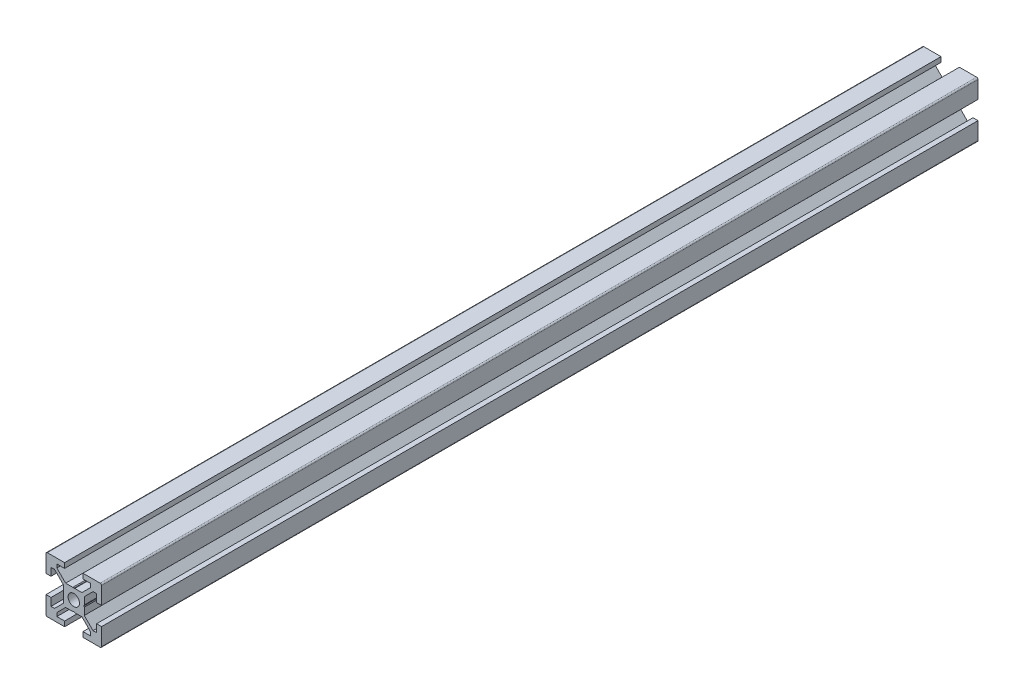
SolidWorks part; units mm, degrees
ref_plane "Front Plane" through (0, 0, 0) normal (0, 0, 1) x (1, 0, 0)
ref_plane "Top Plane" through (0, 0, 0) normal (0, 1, 0) x (1, 0, 0)
ref_plane "Right Plane" through (0, 0, 0) normal (1, 0, 0) x (0, 0, -1)
sketch "Sketch1" plane through (0, 0, 0) normal (0, 0, 1) x (1, 0, 0)
  line L0 (-3.3, 10) -> (-3.3, 8.2)
  line L1 (0, 0) -> (50000, 0) construction
  line L2 (-10, 3.3) -> (-10, 10)
  line L3 (-10, 10) -> (-3.3, 10)
  line L4 (0, 0) -> (0, 50000) construction
  line L5 (-10, -10) -> (10, 10) construction
  line L6 (-10, 10) -> (10, -10) construction
  line L7 (-2.9315, -3.78) -> (-0.34, -3.78)
  line L8 (-3.78, -2.9315) -> (-3.78, -0.34)
  line L9 (-2.9315, 3.78) -> (-0.34, 3.78)
  line L10 (3.78, -2.9315) -> (3.78, -0.34)
  line L11 (-3.78, -3.78) -> (3.78, 3.78) construction
  line L12 (-3.78, 3.78) -> (3.78, -3.78) construction
  line L13 (-6.08, 8.2) -> (-3.3, 8.2)
  line L14 (-8.2, 6.08) -> (-8.2, 3.3)
  line L15 (-8.2, 3.3) -> (-10, 3.3)
  line L16 (-8.2, 6.08) -> (-6.9285, 6.08)
  line L17 (-6.08, 8.2) -> (-6.08, 6.9285)
  line L18 (-6.9285, 6.08) -> (-3.78, 2.9315)
  line L19 (-6.08, 6.9285) -> (-2.9315, 3.78)
  line L20 (8.2, 6.08) -> (6.9285, 6.08)
  line L21 (8.2, 6.08) -> (8.2, 3.3)
  line L22 (8.2, 3.3) -> (10, 3.3)
  line L23 (10, 3.3) -> (10, 10)
  line L24 (10, 10) -> (3.3, 10)
  line L25 (3.3, 10) -> (3.3, 8.2)
  line L26 (6.08, 8.2) -> (3.3, 8.2)
  line L27 (6.08, 8.2) -> (6.08, 6.9285)
  line L28 (6.08, 6.9285) -> (2.9315, 3.78)
  line L29 (6.9285, 6.08) -> (3.78, 2.9315)
  line L30 (6.9285, -6.08) -> (3.78, -2.9315)
  line L31 (6.08, -6.9285) -> (2.9315, -3.78)
  line L32 (6.08, -8.2) -> (6.08, -6.9285)
  line L33 (6.08, -8.2) -> (3.3, -8.2)
  line L34 (3.3, -10) -> (3.3, -8.2)
  line L35 (10, -10) -> (3.3, -10)
  line L36 (10, -3.3) -> (10, -10)
  line L37 (8.2, -3.3) -> (10, -3.3)
  line L38 (8.2, -6.08) -> (8.2, -3.3)
  line L39 (8.2, -6.08) -> (6.9285, -6.08)
  line L40 (-6.08, -6.9285) -> (-2.9315, -3.78)
  line L41 (-6.9285, -6.08) -> (-3.78, -2.9315)
  line L42 (-6.08, -8.2) -> (-6.08, -6.9285)
  line L43 (-8.2, -6.08) -> (-6.9285, -6.08)
  line L44 (-8.2, -3.3) -> (-10, -3.3)
  line L45 (-8.2, -6.08) -> (-8.2, -3.3)
  line L46 (-6.08, -8.2) -> (-3.3, -8.2)
  line L47 (-10, -10) -> (-3.3, -10)
  line L48 (-10, -3.3) -> (-10, -10)
  line L49 (-3.3, -10) -> (-3.3, -8.2)
  line L50 (-0.34, 3.78) -> (0, 3.66)
  line L51 (0.34, 3.78) -> (0, 3.66)
  line L52 (0.34, 3.78) -> (2.9315, 3.78)
  line L53 (-3.78, -0.34) -> (-3.66, 0)
  line L54 (-3.78, 0.34) -> (-3.66, 0)
  line L55 (3.78, 0.34) -> (3.66, 0)
  line L56 (3.78, -0.34) -> (3.66, 0)
  line L57 (-0.34, -3.78) -> (0, -3.66)
  line L58 (0.34, -3.78) -> (0, -3.66)
  line L59 (3.78, 0.34) -> (3.78, 2.9315)
  line L60 (0.34, -3.78) -> (2.9315, -3.78)
  line L61 (-3.78, 0.34) -> (-3.78, 2.9315)
  circle A0 centre (0, 0) radius 2.05
  point P0 (0, 0)
  dimension "D3" = 4.1
  dimension "D1" = 20
  dimension "D2" = 20
  dimension "D4" = 7.56
  dimension "D5" = 6.7
  dimension "D6" = 6.7
  dimension "D7" = 0.6
  dimension "D8" = 3.92
  dimension "D9" = 0.34
  dimension "D10" = 0.12
extrude "Boss-Extrude1" add sketch "Sketch1" along normal blind 157.75
fillet "Fillet1" radius 0.5 4 edges at (-10, 10, 78.875) (-10, -10, 78.875) (10, -10, 78.875) (10, 10, 78.875)
mirror "Mirror2" about plane through (0, 0, 157.75) normal (0, 0, 1) of "Boss-Extrude1", "Fillet1"
